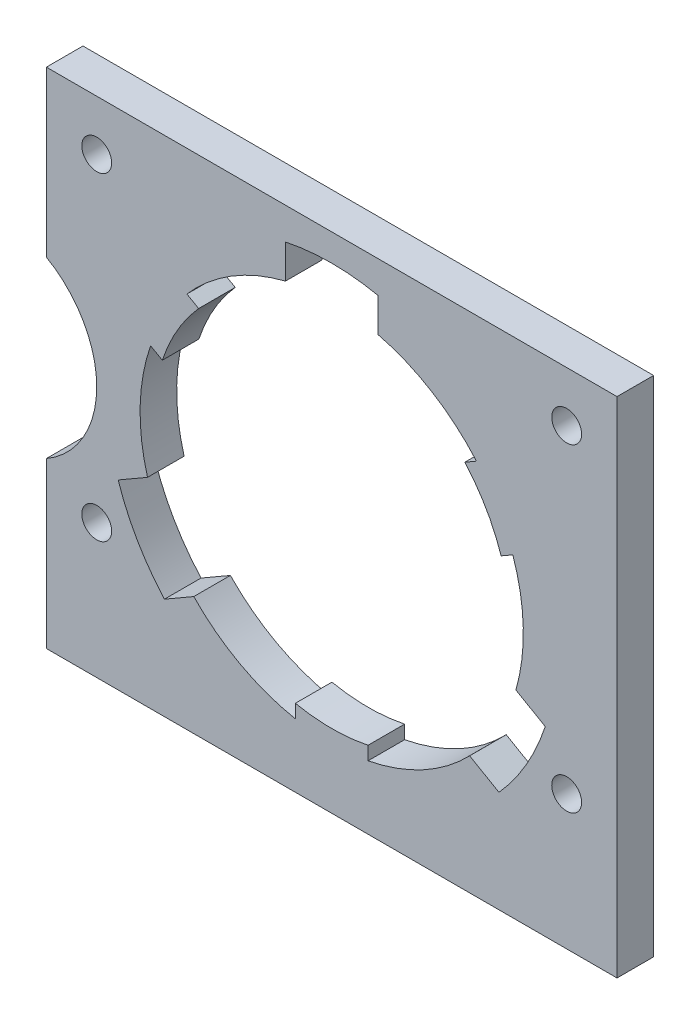
SolidWorks part; units mm, degrees
material "Acrylic (Medium-high impact)"
ref_plane "Front Plane" through (0, 0, 0) normal (0, 0, 1) x (1, 0, 0)
ref_plane "Top Plane" through (0, 0, 0) normal (0, 1, 0) x (1, 0, 0)
ref_plane "Right Plane" through (0, 0, 0) normal (1, 0, 0) x (0, 0, -1)
sketch "Sketch1" plane through (0, 0, 0) normal (0, 0, 1) x (1, 0, 0)
  line L1 (-21.59, 19.05) -> (21.59, 19.05)
  line L2 (-21.59, 19.05) -> (-21.59, -19.05)
  line L3 (-21.59, -19.05) -> (21.59, -19.05)
  line L4 (21.59, 19.05) -> (21.59, -19.05)
  line L5 (-21.59, 19.05) -> (21.59, -19.05) construction
  line L6 (-21.59, -19.05) -> (21.59, 19.05) construction
  point P0 (0, 0)
  dimension "D1" = 43.18
  dimension "D2" = 38.1
extrude "Boss-Extrude1" add sketch "Sketch1" along normal blind 2.7686
sketch "Sketch2" plane through (0, 0, 2.7686) normal (0, 0, 1) x (1, 0, 0)
  line L0 (-21.59, -19.05) -> (21.59, -19.05) construction
  circle A0 centre (0, 0) radius 14.5
  dimension "D1" = 19.05
  dimension "D2" = 29
extrude "Cut-Extrude1" cut sketch "Sketch2" against normal through all
sketch "Sketch3" plane through (0, 0, 2.7686) normal (0, 0, 1) x (1, 0, 0)
  line L0 (-3.5, 16.6358) -> (-3.5, 14.0712)
  line L1 (3.5, 16.6358) -> (3.5, 14.0712)
  arc A0 (3.5, 16.6358) -> (-3.5, 16.6358) centre (0, 0) ccw
  arc A1 (3.5, 14.0712) -> (-3.5, 14.0712) centre (0, 0) ccw
  circle A2 centre (0, 0) radius 14.5 construction
  dimension "D1" = 34
  dimension "D2" = 7
extrude "Cut-Extrude2" cut sketch "Sketch3" against normal through all
pattern_circular "CirPattern1" count 3 over 360 about axis through (0, 0, 0) along (0, 0, 1) of "Cut-Extrude2"
sketch "Sketch4" plane through (0, 0, 2.7686) normal (0, 0, 1) x (1, 0, 0)
  line L0 (-2.75, -13.2169) -> (-2.75, -14.2368)
  line L2 (2.75, -13.2169) -> (2.75, -14.2368)
  arc A0 (-2.75, -13.2169) -> (2.75, -13.2169) centre (0, 0) ccw
  arc A1 (-2.75, -14.2368) -> (2.75, -14.2368) centre (0, 0) ccw
  arc A2 (-10.4361, -10.0667) -> (10.4361, -10.0667) centre (0, 0) ccw construction
  dimension "D1" = 27
  dimension "D2" = 5.5
extrude "Boss-Extrude2" add sketch "Sketch4" against normal up to surface (2.7686 mm away) up to face at (0, 0, 0)
pattern_circular "CirPattern2" count 3 over 360 about axis through (0, 0, 0) along (0, 0, 1) of "Boss-Extrude2"
sketch "Sketch6" plane through (0, 0, 2.7686) normal (0, 0, 1) x (1, 0, 0)
  circle A0 centre (-25.4, 0) radius 7.62
  dimension "D1" = 25.4
  dimension "D2" = 15.24
extrude "Cut-Extrude4" cut sketch "Sketch6" against normal through all
hole_wizard "#4-40 Tapped Hole1" positions "Sketch7" profile "Sketch8" tap size "#4-40" standard "ANSI Inch" end condition through all
sketch "Sketch7" plane through (0, 0, 0) normal (0, 0, -1) x (-1, 0, 0)
  line L0 (-21.59, -19.05) -> (-21.59, 19.05) construction
  line L1 (21.59, -19.05) -> (-21.59, -19.05) construction
  line L2 (-21.59, 19.05) -> (21.59, 19.05) construction
  line L3 (21.59, 19.05) -> (21.59, 6.5991) construction
  point P0 (-17.78, 15.24)
  point P2 (-17.78, -8.89)
  point P4 (17.78, -8.89)
  point P6 (17.78, 15.24)
  dimension "D1" = 3.81
  dimension "D2" = 10.16
  dimension "D3" = 3.81
  dimension "D4" = 3.81
sketch "Sketch8" plane through (17.78, 15.24, 0) normal (1, 0, 0) x (0, 1, 0)
  line L0 (0, 0) -> (0, 2.7686)
  line L1 (0, 2.7686) -> (1.1303, 2.7686)
  line L2 (1.1303, 2.7686) -> (1.1303, 0)
  line L5 (1.1303, 0) -> (0, 0)
  line L11 (0, -6.35) -> (0, 107.95) construction
  dimension "Thread Major Dia." = 2.2606
  dimension "Thru Tap Drill Depth" = 2.7686
